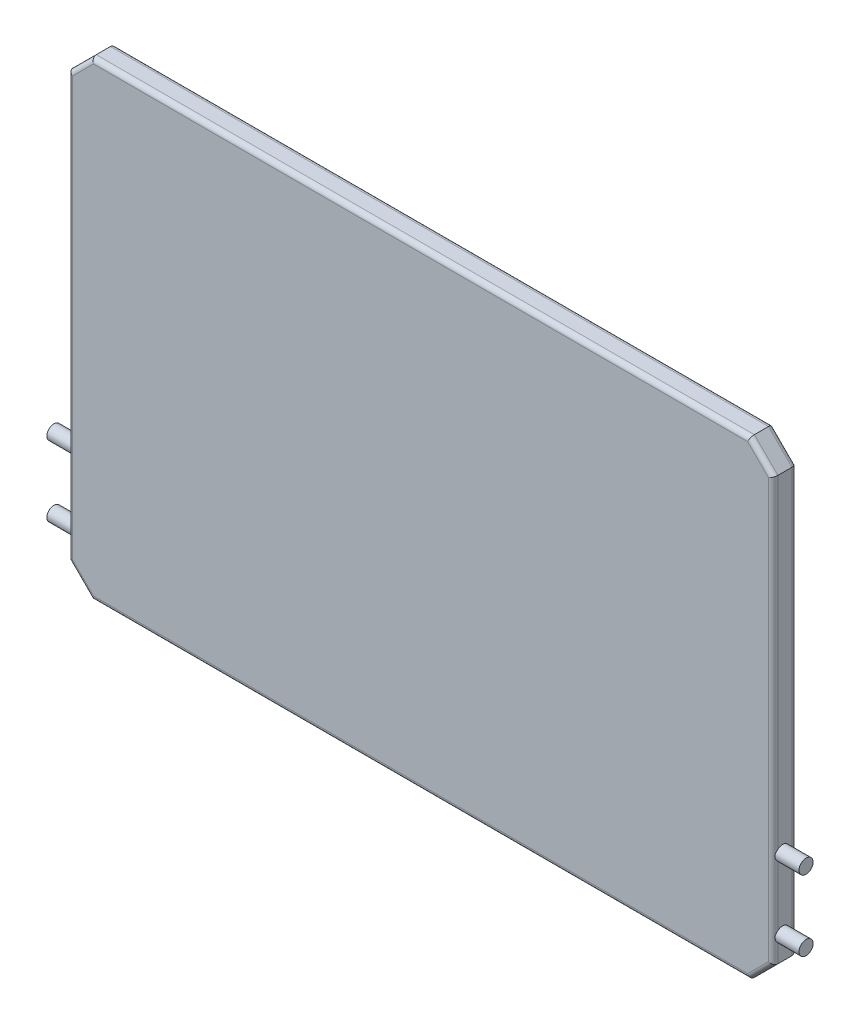
SolidWorks part; units mm, degrees
ref_plane "Front Plane" through (0, 0, 0) normal (0, 0, 1) x (1, 0, 0)
ref_plane "Top Plane" through (0, 0, 0) normal (0, 1, 0) x (1, 0, 0)
ref_plane "Right Plane" through (0, 0, 0) normal (1, 0, 0) x (0, 0, -1)
sketch "Sketch1" plane through (0, 0, 0) normal (0, 0, 1) x (1, 0, 0)
  line L0 (0, 1000) -> (0, -1000) construction
  line L1 (1500, -1000) -> (-1500, -1000)
  line L2 (1500, -1000) -> (1500, 1000)
  line L3 (1500, 1000) -> (-1500, 1000)
  line L4 (-1500, -1000) -> (-1500, 1000)
  line L5 (1500, -1000) -> (-1500, 1000) construction
  line L6 (1500, 1000) -> (-1500, -1000) construction
  line L7 (-1500, 0) -> (1500, 0) construction
  point P0 (0, 0)
  dimension "D1" = 2000
  dimension "D2" = 3000
extrude "Boss-Extrude1" add sketch "Sketch1" along normal mid plane 100
sketch "Sketch3" plane through (0, 0, 0) normal (1, 0, 0) x (0, 0, -1)
  line L0 (-50, -1000) -> (50, -1000) construction
  circle A0 centre (-10, -500) radius 30
  circle A1 centre (-10, -800) radius 30
  point P3 (0, 0)
  point P8 (0, 0)
  point P9 (0, 0)
  dimension "D2" = 60
  dimension "D1" = 200
  dimension "D3" = 10
  dimension "D4" = 500
chamfer "Chamfer1" distance 100 angle 45 4 edges at (-1500, -1000, 0) (1500, -1000, 0) (1500, 1000, 0) (-1500, 1000, 0)
fillet "Fillet1" radius 20 16 edges at (1450, -950, -50) (1500, 0, -50) (1450, 950, -50) (0, 1000, -50) (-1450, 950, -50) (-1500, 0, -50) (-1450, -950, -50) (0, -1000, -50) (-1450, 950, 50) (0, 1000, 50) (1450, 950, 50) (1500, 0, 50) (1450, -950, 50) (0, -1000, 50) (-1450, -950, 50) (-1500, 0, 50)
extrude "Boss-Extrude2" add sketch "Sketch3" along normal mid plane 3200 from offset 0
